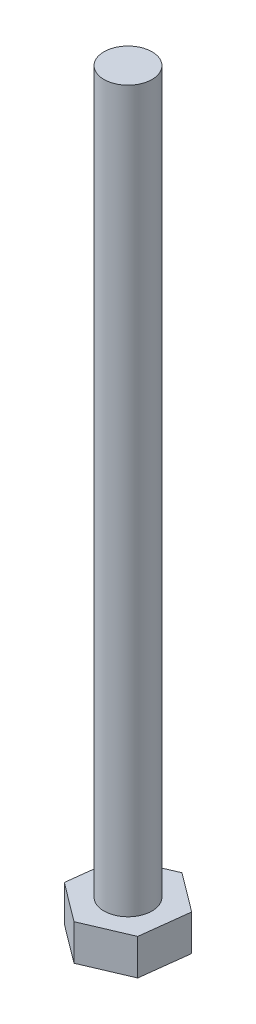
SolidWorks part; units mm, degrees
ref_plane "Front Plane" through (0, 0, 0) normal (0, 0, 1) x (1, 0, 0)
ref_plane "Top Plane" through (0, 0, 0) normal (0, 1, 0) x (1, 0, 0)
ref_plane "Right Plane" through (0, 0, 0) normal (1, 0, 0) x (0, 0, -1)
sketch "Sketch1" plane through (0, 0, 0) normal (0, 1, 0) x (1, 0, 0)
  line L1 (3.2332, -2.4249) -> (3.7166, 1.5876)
  line L2 (3.7166, 1.5876) -> (0.4834, 4.0124)
  line L3 (0.4834, 4.0124) -> (-3.2332, 2.4249)
  line L4 (-3.2332, 2.4249) -> (-3.7166, -1.5876)
  line L5 (-3.7166, -1.5876) -> (-0.4834, -4.0124)
  line L6 (-0.4834, -4.0124) -> (3.2332, -2.4249)
  circle A0 centre (0, 0) radius 3.5 construction
  dimension "D1" = 7
extrude "Boss-Extrude1" add sketch "Sketch1" along normal blind 3
sketch "Sketch2" plane through (0, 3, 0) normal (0, 1, 0) x (1, 0, 0)
  circle A0 centre (0, 0) radius 2
  dimension "D1" = 4
extrude "Boss-Extrude2" add sketch "Sketch2" along normal blind 60
